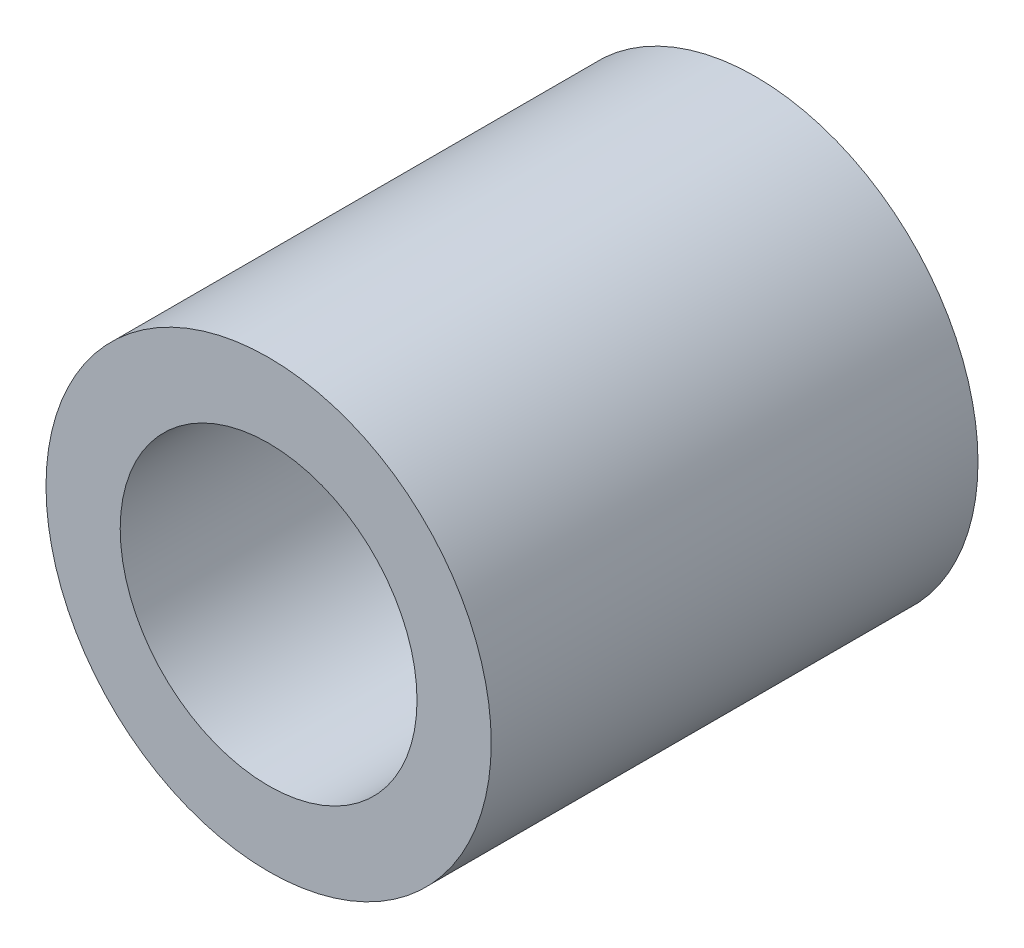
SolidWorks part; units mm, degrees
material "6061 Alloy"
ref_plane "Front" through (0, 0, 0) normal (0, 0, 1) x (1, 0, 0)
ref_plane "Top" through (0, 0, 0) normal (0, 1, 0) x (1, 0, 0)
ref_plane "Right" through (0, 0, 0) normal (1, 0, 0) x (0, 0, -1)
sketch "Sketch2" plane through (0, 0, 0) normal (0, 0, 1) x (1, 0, 0)
  circle A0 centre (0, 0) radius 375
  circle A1 centre (0, 0) radius 250
  dimension "D1" = 750
  dimension "D2" = 500
extrude "Boss-Extrude1" add sketch "Sketch2" along normal blind 820
